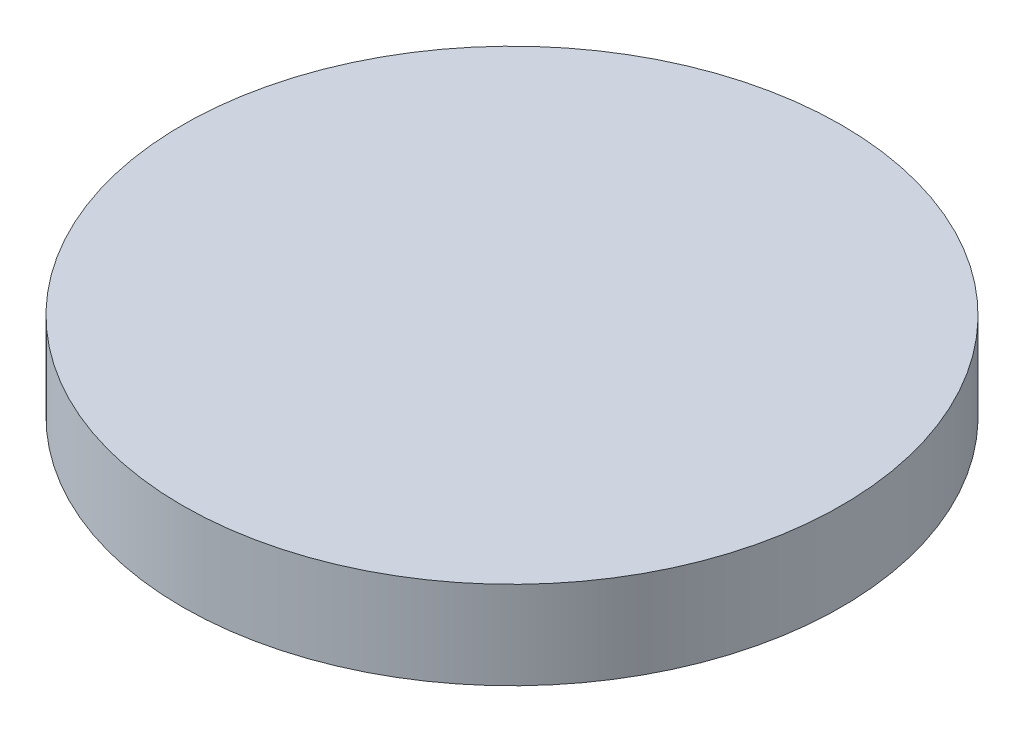
SolidWorks part; units mm, degrees
material "Plain Carbon Steel"
ref_plane "Front Plane" through (0, 0, 0) normal (0, 0, 1) x (1, 0, 0)
ref_plane "Top Plane" through (0, 0, 0) normal (0, 1, 0) x (1, 0, 0)
ref_plane "Right Plane" through (0, 0, 0) normal (1, 0, 0) x (0, 0, -1)
sketch "Sketch1" plane through (0, 0, 0) normal (0, 1, 0) x (1, 0, 0)
  circle A0 centre (0, 0) radius 19.05
  dimension "D1" = 38.1
extrude "Boss-Extrude1" add sketch "Sketch1" along normal blind 5.08
